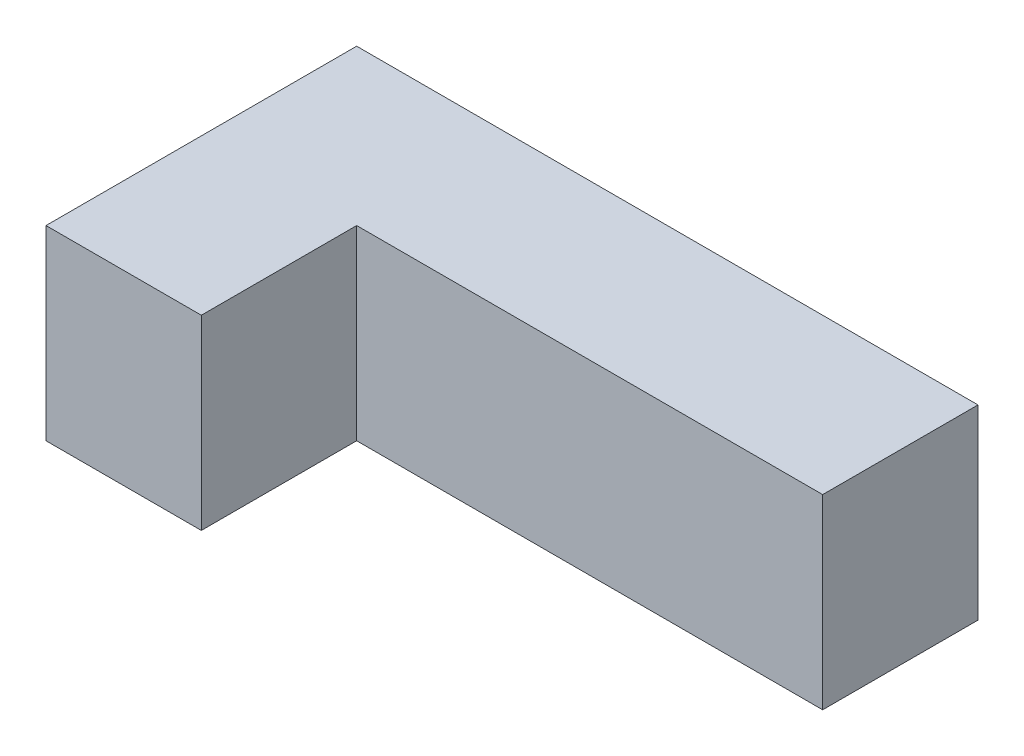
SolidWorks part; units mm, degrees
ref_plane "Přední rovina" through (0, 0, 0) normal (0, 0, 1) x (1, 0, 0)
ref_plane "Horní rovina" through (0, 0, 0) normal (0, 1, 0) x (1, 0, 0)
ref_plane "Pravá rovina" through (0, 0, 0) normal (1, 0, 0) x (0, 0, -1)
sketch "Skica1" plane through (0, 0, 0) normal (0, 1, 0) x (1, 0, 0)
  line L0 (0, 0) -> (0, 50)
  line L1 (0, 50) -> (100, 50)
  line L2 (100, 50) -> (100, 25)
  line L3 (100, 25) -> (25, 25)
  line L4 (25, 25) -> (25, 0)
  line L5 (25, 0) -> (0, 0)
  dimension "D1" = 50
  dimension "D2" = 100
  dimension "D3" = 75
  dimension "D4" = 25
extrude "Přidat vysunutím1" add sketch "Skica1" along normal blind 30
